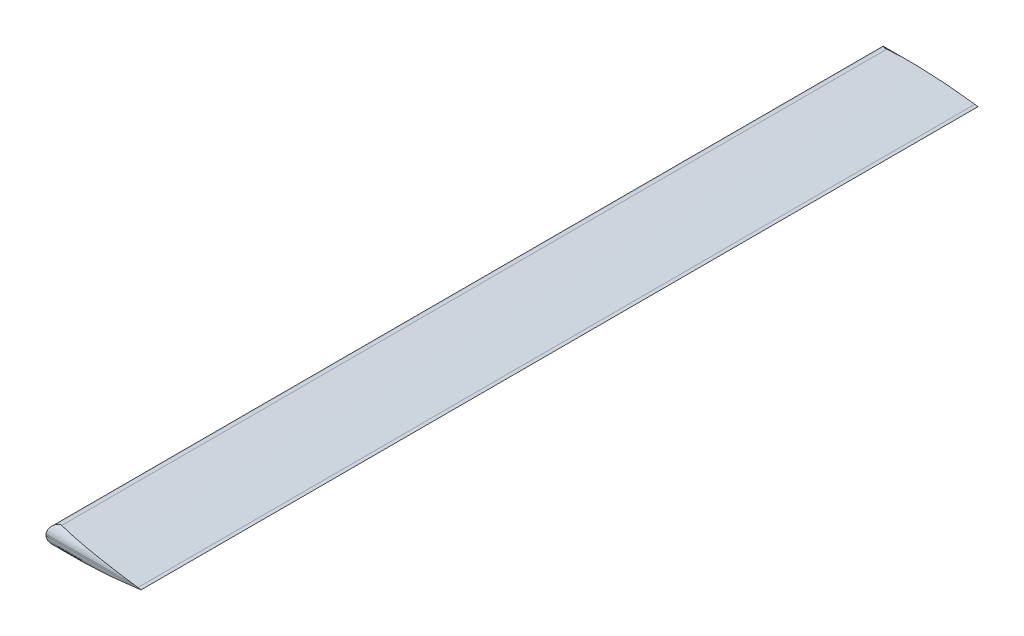
SolidWorks part; units mm, degrees
ref_plane "Front Plane" through (0, 0, 0) normal (0, 0, 1) x (1, 0, 0)
ref_plane "Top Plane" through (0, 0, 0) normal (0, 1, 0) x (1, 0, 0)
ref_plane "Right Plane" through (0, 0, 0) normal (1, 0, 0) x (0, 0, -1)
sketch "Sketch2" plane through (0, 0, 125) normal (0, 0, 1) x (1, 0, 0)
  line L6 (72.8985, 242.6983) -> (74.0667, 242.8596)
  line L7 (74.0667, 242.8596) -> (72.8985, 243.0209)
  arc A0 (42.4402, 246.6168) -> (42.4403, 239.1025) centre (44.0667, 242.8596) ccw
  spline S4 degree 3 poles (72.8985, 243.0209) (68.2268, 243.666) (58.8702, 244.8607) (48.7077, 245.9849) (43.2279, 246.5384) (42.4402, 246.6168) knots 0.003074 0.003074 0.003074 0.003074 0.064763 0.126452 0.136805 0.136805 0.136805 0.136805
  spline S5 degree 3 poles (42.4403, 239.1025) (43.2279, 239.1809) (48.7077, 239.7343) (58.8701, 240.8588) (68.2267, 242.0534) (72.8985, 242.6983) knots 0.856366 0.856366 0.856366 0.856366 0.866719 0.928408 0.990097 0.990097 0.990097 0.990097
extrude "Boss-Extrude1" add sketch "Sketch2" along normal mid plane 300
fillet "Fillet1" radius 3 2 edges at (42.4403, 239.1025, 125) (42.4402, 246.6168, 125)
sketch "Sketch3" plane through (0, 242.8596, 0) normal (0, -1, 0) x (1, 0, 0)
  line L0 (74.0667, 125) -> (21.6985, 125) construction
  line L1 (24.3034, 205) -> (59.3034, 205)
  line L2 (24.3034, 205) -> (24.3034, 185)
  line L3 (24.3034, 185) -> (59.3034, 185)
  line L4 (59.3034, 205) -> (59.3034, 185)
  line L5 (74.0667, 275) -> (74.0667, -25) construction
  line L6 (59.3034, 45) -> (59.3034, 65)
  line L7 (24.3034, 65) -> (59.3034, 65)
  line L8 (24.3034, 45) -> (24.3034, 65)
  line L9 (24.3034, 45) -> (59.3034, 45)
extrude "Cut-Extrude1" cut sketch "Sketch3" along normal through all
sketch "Sketch5" plane through (-140.0326, 0, 0) normal (-1, 0, 0) x (0, 0, 1)
  line L0 (271, 246.923) -> (277, 246.923)
  line L1 (277, 246.923) -> (277, 238.7962)
  line L2 (277, 238.7962) -> (271, 238.7962)
  line L3 (-21, 246.923) -> (-27, 246.923)
  line L4 (-25, 243.1019) -> (-25, 242.6173)
  line L5 (-17, 246.923) -> (-21, 246.923)
  line L6 (-17, 238.7962) -> (-17, 246.923)
  line L7 (-21, 238.7962) -> (-17, 238.7962)
  line L8 (-25, 243.1019) -> (-25, 242.6173)
  line L12 (275, 242.6173) -> (275, 243.1019)
  line L13 (267, 238.7962) -> (271, 238.7962)
  line L14 (267, 246.923) -> (267, 238.7962)
  line L15 (271, 246.923) -> (267, 246.923)
  line L16 (275, 242.6173) -> (275, 243.1019)
  line L20 (-27, 246.923) -> (-27, 238.7962)
  line L21 (-27, 238.7962) -> (-21, 238.7962)
  spline S2 degree 3 poles (3215.8068, -4804.7954) (146.0861, -66.6704) (9.3769, 252.5783) (-22.0681, 246.8019) (-22.3219, 246.7303) (-23.0279, 246.4602) (-23.4482, 246.201) (-23.9838, 245.707) (-24.149, 245.5219) (-24.4405, 245.1181) (-24.5667, 244.9005) (-24.7245, 244.5465) (-24.772, 244.4231) (-24.8535, 244.1721) (-24.8877, 244.0442) (-29.46, 222.4992) (142.7338, 113.3216) (2070.0006, 5860.0379) knots -14.805674 -14.805674 -14.805674 -14.805674 0.125 0.125 0.25 0.25 0.5 0.5 0.625 0.625 0.75 0.75 0.8125 0.8125 0.875 0.875 11.12682 11.12682 11.12682 11.12682 only from (-21, 246.923) to (-25, 243.1019)
  spline S3 degree 3 poles (5610.5556, 2300.2922) (471.6326, 450.7834) (-32.5298, 277.9624) (-24.8617, 241.5502) (-24.7787, 241.2955) (-24.57, 240.8252) (-24.4423, 240.6041) (-24.1507, 240.1994) (-23.9882, 240.0168) (-23.6298, 239.6853) (-23.4345, 239.5375) (-23.0203, 239.2817) (-22.8001, 239.1723) (-22.3252, 238.9899) (-22.0756, 238.9191) (-1.4797, 235.1014) (103.4228, 367.6329) (-5679.4799, 2222.8802) knots -17.170062 -17.170062 -17.170062 -17.170062 0.125 0.125 0.25 0.25 0.375 0.375 0.5 0.5 0.625 0.625 0.75 0.75 0.875 0.875 10.592197 10.592197 10.592197 10.592197 only from (-25, 242.6173) to (-21, 238.7962)
  spline S4 degree 3 poles (-21, 246.923) (-21.2775, 246.923) (-21.546, 246.8978) (-22.0681, 246.8019) (-22.3219, 246.7303) (-23.0279, 246.4602) (-23.4482, 246.201) (-23.9838, 245.707) (-24.149, 245.5219) (-24.4405, 245.1181) (-24.5667, 244.9005) (-24.7245, 244.5465) (-24.772, 244.4231) (-24.8535, 244.1721) (-24.8877, 244.0442) (-24.9709, 243.6525) (-25, 243.3784) (-25, 243.1019) knots 0 0 0 0 0.125 0.125 0.25 0.25 0.5 0.5 0.625 0.625 0.75 0.75 0.8125 0.8125 0.875 0.875 1 1 1 1
  spline S5 degree 3 poles (-25, 242.6173) (-25, 242.3412) (-24.9717, 242.0727) (-24.8617, 241.5502) (-24.7787, 241.2955) (-24.57, 240.8252) (-24.4423, 240.6041) (-24.1507, 240.1994) (-23.9882, 240.0168) (-23.6298, 239.6853) (-23.4345, 239.5375) (-23.0203, 239.2817) (-22.8001, 239.1723) (-22.3252, 238.9899) (-22.0756, 238.9191) (-21.5524, 238.8221) (-21.2769, 238.7962) (-21, 238.7962) knots 0 0 0 0 0.125 0.125 0.25 0.25 0.375 0.375 0.5 0.5 0.625 0.625 0.75 0.75 0.875 0.875 1 1 1 1
  spline S6 degree 3 poles (5929.6709, 2222.9415) (146.5749, 367.6358) (251.4794, 235.1014) (272.0756, 238.9191) (272.3252, 238.9899) (272.8001, 239.1723) (273.0203, 239.2817) (273.4345, 239.5375) (273.6298, 239.6853) (273.9882, 240.0168) (274.1507, 240.1994) (274.4423, 240.6041) (274.57, 240.8252) (274.7787, 241.2955) (274.8617, 241.5502) (282.5297, 277.9623) (-221.6272, 450.7815) (-5360.4728, 2300.2623) knots -9.592304 -9.592304 -9.592304 -9.592304 0.125 0.125 0.25 0.25 0.375 0.375 0.5 0.5 0.625 0.625 0.75 0.75 0.875 0.875 18.169969 18.169969 18.169969 18.169969 only from (271, 238.7962) to (275, 242.6173)
  spline S7 degree 3 poles (-1819.9479, 5859.8806) (107.2693, 113.3236) (279.46, 222.4994) (274.8877, 244.0442) (274.8535, 244.1721) (274.772, 244.4231) (274.7245, 244.5465) (274.5667, 244.9005) (274.4405, 245.1181) (274.149, 245.5219) (273.9838, 245.707) (273.4482, 246.201) (273.0279, 246.4602) (272.3219, 246.7303) (272.0681, 246.8019) (240.6235, 252.5782) (103.9173, -66.6624) (-2965.6925, -4804.619) knots -10.126726 -10.126726 -10.126726 -10.126726 0.125 0.125 0.1875 0.1875 0.25 0.25 0.375 0.375 0.5 0.5 0.75 0.75 0.875 0.875 15.805488 15.805488 15.805488 15.805488 only from (275, 243.1019) to (271, 246.923)
  spline S8 degree 3 poles (271, 238.7962) (271.2769, 238.7962) (271.5524, 238.8221) (272.0756, 238.9191) (272.3252, 238.9899) (272.8001, 239.1723) (273.0203, 239.2817) (273.4345, 239.5375) (273.6298, 239.6853) (273.9882, 240.0168) (274.1507, 240.1994) (274.4423, 240.6041) (274.57, 240.8252) (274.7787, 241.2955) (274.8617, 241.5502) (274.9717, 242.0727) (275, 242.3412) (275, 242.6173) knots 0 0 0 0 0.125 0.125 0.25 0.25 0.375 0.375 0.5 0.5 0.625 0.625 0.75 0.75 0.875 0.875 1 1 1 1
  spline S9 degree 3 poles (275, 243.1019) (275, 243.3784) (274.9709, 243.6525) (274.8877, 244.0442) (274.8535, 244.1721) (274.772, 244.4231) (274.7245, 244.5465) (274.5667, 244.9005) (274.4405, 245.1181) (274.149, 245.5219) (273.9838, 245.707) (273.4482, 246.201) (273.0279, 246.4602) (272.3219, 246.7303) (272.0681, 246.8019) (271.546, 246.8978) (271.2775, 246.923) (271, 246.923) knots 0 0 0 0 0.125 0.125 0.1875 0.1875 0.25 0.25 0.375 0.375 0.5 0.5 0.75 0.75 0.875 0.875 1 1 1 1
  dimension "D1" = 0
  dimension "D2" = 0
extrude "Cut-Extrude2" cut sketch "Sketch5" against normal through all
fillet "Fillet2" radius 3 4 edges at (59.3034, 241.905, 185) (59.3034, 241.905, 205) (59.3034, 241.905, 65) (59.3034, 241.905, 45)
